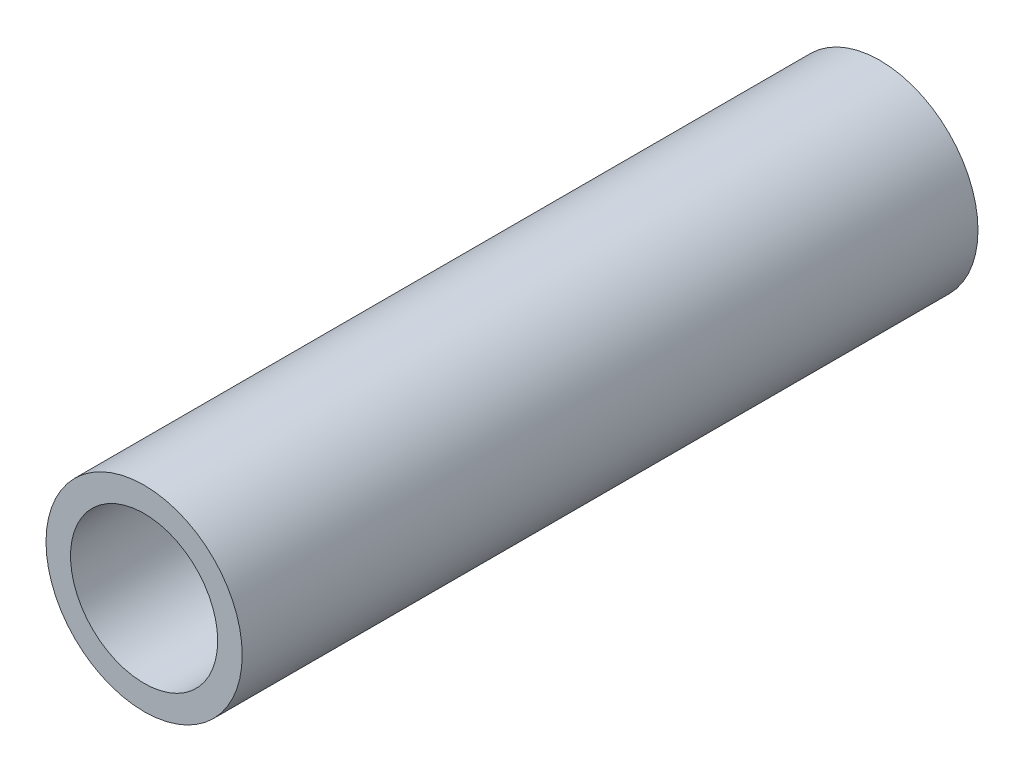
SolidWorks part; units mm, degrees
ref_plane "Ebene vorne" through (0, 0, 0) normal (0, 0, 1) x (1, 0, 0)
ref_plane "Ebene oben" through (0, 0, 0) normal (0, 1, 0) x (1, 0, 0)
ref_plane "Ebene rechts" through (0, 0, 0) normal (1, 0, 0) x (0, 0, -1)
sketch "Skizze1" plane through (0, 0, 0) normal (0, 0, 1) x (1, 0, 0)
  circle A0 centre (0, 0) radius 4
  dimension "D1" = 8
extrude "Aufsatz-Linear austragen1" add sketch "Skizze1" along normal blind 30
shell "Wandung1" thickness 1
